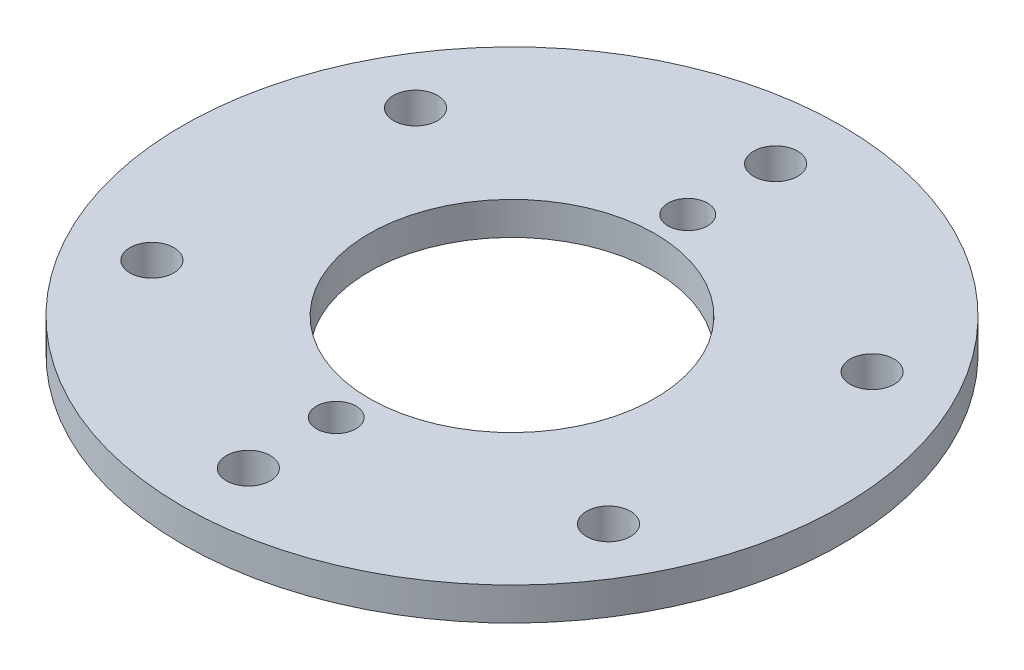
SolidWorks part; units mm, degrees
ref_plane "Front Plane" through (0, 0, 0) normal (0, 0, 1) x (1, 0, 0)
ref_plane "Top Plane" through (0, 0, 0) normal (0, 1, 0) x (1, 0, 0)
ref_plane "Right Plane" through (0, 0, 0) normal (1, 0, 0) x (0, 0, -1)
sketch "Sketch1" plane through (0, 0, 0) normal (0, 1, 0) x (1, 0, 0)
  circle A0 centre (0, 0) radius 150
  circle A1 centre (0, 0) radius 65
  dimension "D1" = 130
  dimension "D2" = 300
extrude "Boss-Extrude1" add sketch "Sketch1" along normal blind 15
hole_wizard "Ø1.0mm Dowel Hole1" positions "Sketch2" profile "Sketch3" hole size "Ø1.0" standard "ISO" end condition through all
sketch "Sketch2" plane through (0, 15, 0) normal (0, 1, 0) x (1, 0, 0)
  point P0 (0, 120)
  dimension "D1" = 120
sketch "Sketch3" plane through (0, 15, -120) normal (1, 0, 0) x (0, 0, 1)
  line L0 (0, 0) -> (0, 15)
  line L1 (0, 15) -> (10, 15)
  line L2 (10, 15) -> (10, 0)
  line L5 (10, 0) -> (0, 0)
  line L11 (0, -6.35) -> (0, 107.95) construction
  dimension "Thru Hole Dia." = 20
  dimension "Thru Hole Depth" = 15
pattern_circular "CirPattern1" count 6 over 360 about axis through (0, 0, 0) along (0, 1, 0) of "Ø1.0mm Dowel Hole1"
hole_wizard "Ø1.0mm Dowel Hole2" positions "Sketch4" profile "Sketch5" hole size "Ø1.0" standard "ISO" end condition through all
sketch "Sketch4" plane through (0, 15, 0) normal (0, 1, 0) x (1, 0, 0)
  point P0 (0, 80)
  point P2 (0, -80)
  dimension "D1" = 160
  dimension "D2" = 80
sketch "Sketch5" plane through (0, 15, -80) normal (1, 0, 0) x (0, 0, 1)
  line L0 (0, 0) -> (0, 15)
  line L1 (0, 15) -> (9, 15)
  line L2 (9, 15) -> (9, 0)
  line L5 (9, 0) -> (0, 0)
  line L11 (0, -6.35) -> (0, 107.95) construction
  dimension "Thru Hole Dia." = 18
  dimension "Thru Hole Depth" = 15
